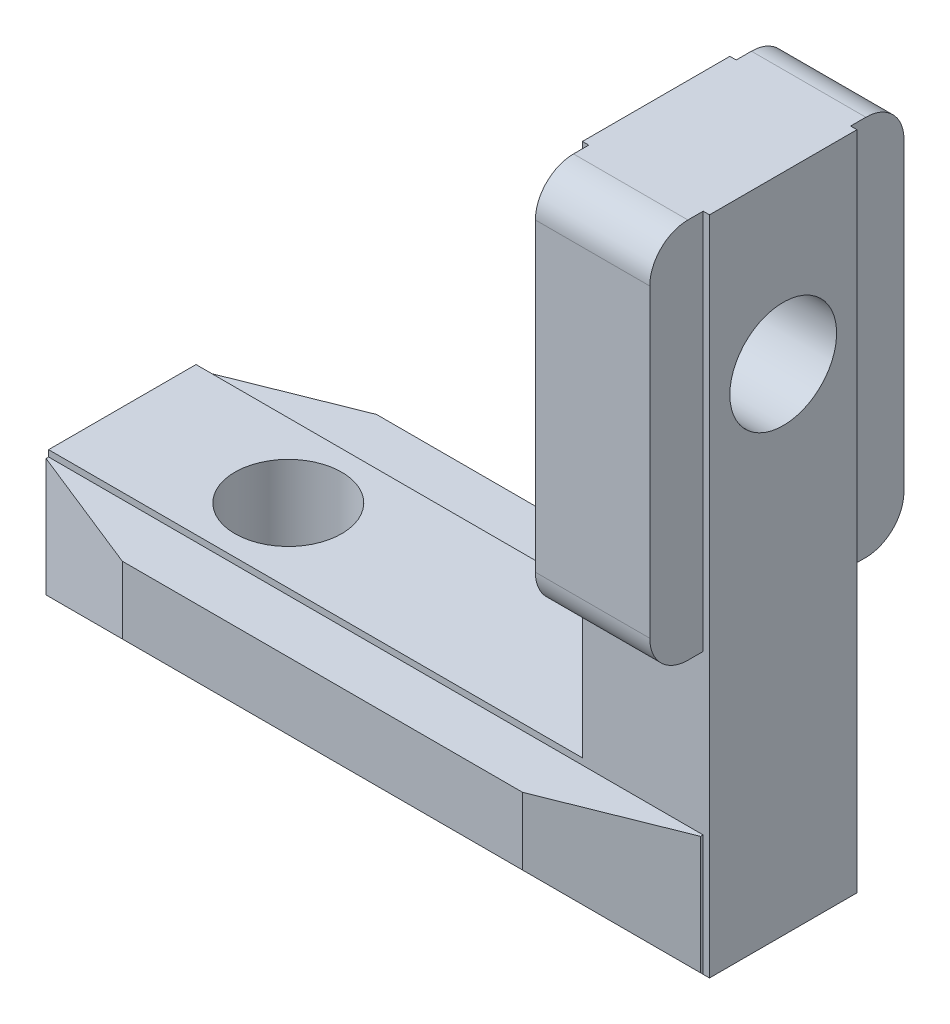
SolidWorks part; units mm, degrees
ref_plane "前视基准面" through (0, 0, 0) normal (0, 0, 1) x (1, 0, 0)
ref_plane "上视基准面" through (0, 0, 0) normal (0, 1, 0) x (1, 0, 0)
ref_plane "右视基准面" through (0, 0, 0) normal (1, 0, 0) x (0, 0, -1)
sketch "草图1" plane through (0, 0, 0) normal (0, 0, 1) x (1, 0, 0)
  line B0 (-26, 0) -> (0, 0)
  line B1 (0, 0) -> (0, 26)
  line B2 (-26, 5) -> (-5, 5)
  line B3 (-5, 5) -> (-5, 26)
  line B4 (-26, 5) -> (-26, 0)
  line B5 (-5, 26) -> (0, 26)
sketch_block_instance "A$C69064533-1"
sketch_block "A$C69064533"
extrude "凸台-拉伸1" add sketch "草图1" along normal mid plane 5.8
sketch "草图3" plane through (-26, 0, 0) normal (-1, 0, 0) x (0, 0, 1)
  line L0 (-2.9, 0) -> (-5, 2.1)
  line L1 (-5, 2.1) -> (-5, 4.75)
  line L2 (-5, 4.75) -> (-2.9, 4.75)
  line L3 (-2.9, 4.75) -> (-2.9, 0)
  line L4 (0, 0) -> (0, 3.3916) construction
  line L5 (2.9, 4.75) -> (2.9, 0)
  line L6 (5, 4.75) -> (2.9, 4.75)
  line L7 (5, 2.1) -> (5, 4.75)
  line L8 (2.9, 0) -> (5, 2.1)
  line L9 (2.9, 5) -> (-2.9, 5) construction
  dimension "D1" = 2.1
  dimension "D2" = 45
  dimension "D3" = 0.25
extrude "凸台-拉伸2" add sketch "草图3" against normal blind 25.75 separate body
chamfer "倒角1" distance 5 distance2 2 1 edges at (-26, 3.425, -5)
chamfer "倒角2" distance 5 distance2 2 1 edges at (-26, 3.425, 5)
chamfer "倒角3" distance 2 distance2 5 1 edges at (-0.25, 3.425, 5)
chamfer "倒角4" distance 2 distance2 5 1 edges at (-0.25, 3.425, -5)
ref_plane "基准面2" through (-2.5, 0, 0) normal (-1, 0, 0) x (0, 0, 1)
sketch "草图4" plane through (-2.5, 0, 0) normal (-1, 0, 0) x (0, 0, 1)
  line L0 (-2.9, 11) -> (-3.5, 11)
  line L1 (-2.9, 26) -> (-2.9, 5) construction
  line L2 (2.9, 26) -> (-2.9, 26) construction
  line L3 (-5, 12.5) -> (-5, 24.5)
  line L4 (-3.5, 26) -> (-2.9, 26)
  line L5 (-2.9, 26) -> (-2.9, 11)
  line L6 (0, 26) -> (0, 16.2673) construction
  line L7 (2.9, 26) -> (2.9, 11)
  line L8 (3.5, 26) -> (2.9, 26)
  line L9 (5, 12.5) -> (5, 24.5)
  line L10 (2.9, 11) -> (3.5, 11)
  arc A0 (-5, 24.5) -> (-3.5, 26) centre (-3.5, 24.5) cw
  arc A1 (-3.5, 11) -> (-5, 12.5) centre (-3.5, 12.5) cw
  arc A2 (3.5, 11) -> (5, 12.5) centre (3.5, 12.5) ccw
  arc A3 (5, 24.5) -> (3.5, 26) centre (3.5, 24.5) ccw
  point P13 (-5, 11)
  point P25 (5, 11)
  dimension "D3" = 1.5
  dimension "D1" = 2.1
  dimension "D2" = 15
extrude "凸台-拉伸3" add sketch "草图4" along normal mid plane 4.5
sketch "草图5" plane through (0, 5, 0) normal (0, 1, 0) x (1, 0, 0)
  line L0 (0, -2.9) -> (0, 2.9) construction
  point P0 (-19.47, 0)
  dimension "D1" = 19.47
hole_wizard "M5 螺纹孔1" positions "3D草图1" profile "草图6" tap size "M5" standard "Iso"
sketch3d "3D草图1"
  point P0 (-19.47, 5, 0)
sketch "草图6" plane through (-19.47, 5, 0) normal (1, 0, 0) x (0, 0, 1)
  line L0 (0, 0) -> (0, 28.6618)
  line L1 (0, 28.6618) -> (2.1, 27.4)
  line L2 (2.1, 27.4) -> (2.1, 0)
  line L5 (2.1, 0) -> (0, 0)
  line L10 (0, 28.6618) -> (-2.1, 27.4) construction
  line L11 (0, -6.35) -> (0, 107.95) construction
  dimension "螺纹孔钻头直径" = 4.2
  dimension "螺纹孔钻头深度" = 27.4
  dimension "导头角度" = 118
cosmetic thread "孔螺蚊线1" parameters "D1"=5, "D2"=5
ref_plane "基准面3" through (0, 0, 0) normal (-0.7071, -0.7071, 0) x (-0.7071, 0.7071, 0)
mirror "镜向1" about plane through (0, 0, 0) normal (-0.7071, -0.7071, 0) of "M5 螺纹孔1"
